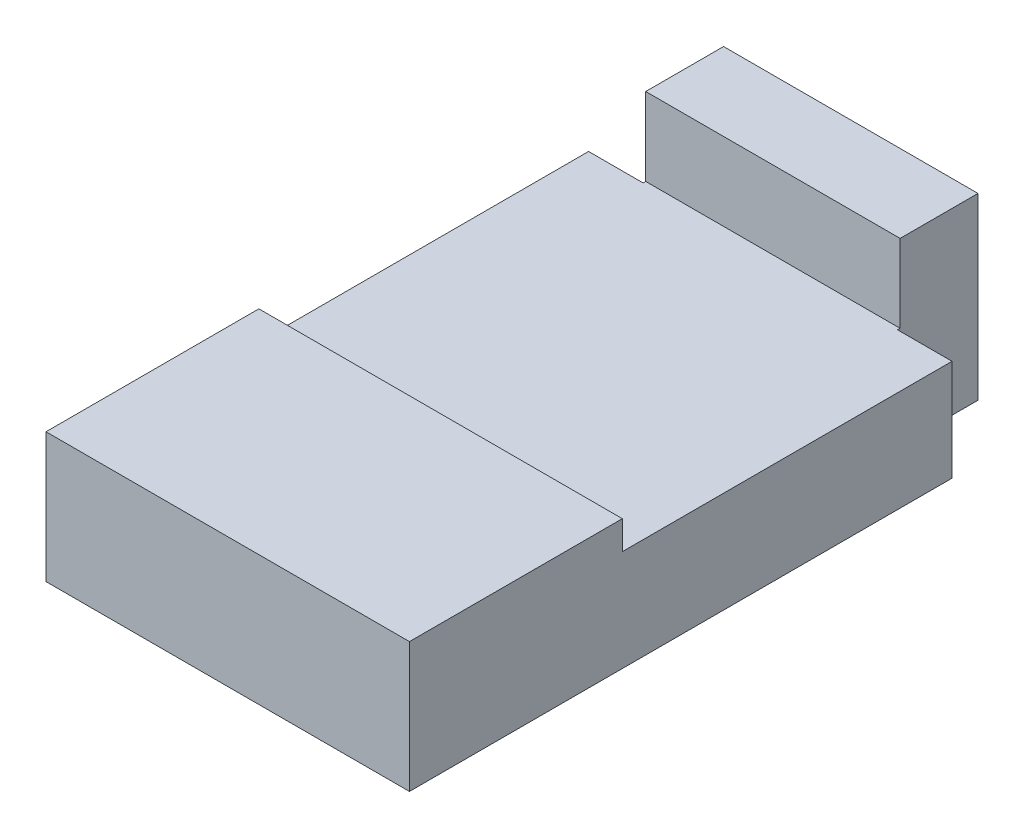
SolidWorks part; units mm, degrees
ref_plane "Front Plane" through (0, 0, 0) normal (0, 0, 1) x (1, 0, 0)
ref_plane "Top Plane" through (0, 0, 0) normal (0, 1, 0) x (1, 0, 0)
ref_plane "Right Plane" through (0, 0, 0) normal (1, 0, 0) x (0, 0, -1)
sketch "Sketch1" plane through (0, 0, 0) normal (0, 0, 1) x (1, 0, 0)
  line L1 (-2.45, -0.975) -> (2.45, -0.975)
  line L2 (-2.45, -0.975) -> (-2.45, 0.975)
  line L3 (-2.45, 0.975) -> (2.45, 0.975)
  line L4 (2.45, -0.975) -> (2.45, 0.975)
  line L5 (-2.45, -0.975) -> (2.45, 0.975) construction
  line L6 (-2.45, 0.975) -> (2.45, -0.975) construction
  point P0 (0, 0)
  dimension "D1" = 1.95
  dimension "D2" = 4.9
extrude "Boss-Extrude1" add sketch "Sketch1" along normal blind 9 and the other way blind 3
sketch "Sketch2" plane through (0, 0.975, 0) normal (0, 1, 0) x (1, 0, 0)
  line L0 (2.45, 3) -> (2.45, -9) construction
  line L1 (-2.45, 3) -> (2.45, 3)
  line L2 (-2.45, 3) -> (-2.45, 1.5)
  line L3 (-2.45, 1.5) -> (2.45, 1.5)
  line L4 (2.45, 3) -> (2.45, 1.5)
  dimension "D1" = 1.5
extrude "Boss-Extrude2" add sketch "Sketch2" along normal blind 1.5
sketch "Sketch3" plane through (0, 0, 0) normal (1, 0, 0) x (0, 0, -1)
  line L0 (1.5, 0.975) -> (-9, 0.975) construction
  line L1 (-9, -0.975) -> (1.45, -0.975)
  line L2 (-9, -0.975) -> (-9, 0.975)
  line L3 (-9, 0.975) -> (1.45, 0.975)
  line L4 (1.45, -0.975) -> (1.45, 0.975)
  dimension "D1" = 10.45
extrude "Boss-Extrude3" add sketch "Sketch3" along normal mid plane 7
sketch "Sketch4" plane through (0, 0.975, 0) normal (0, 1, 0) x (1, 0, 0)
  line L0 (3.5, 1.45) -> (3.5, -9) construction
  line L1 (-3.5, -9) -> (3.5, -9)
  line L2 (-3.5, -9) -> (-3.5, -4.9)
  line L3 (-3.5, -4.9) -> (3.5, -4.9)
  line L4 (3.5, -9) -> (3.5, -4.9)
  dimension "D1" = 4.1
extrude "Boss-Extrude4" add sketch "Sketch4" along normal blind 0.55
